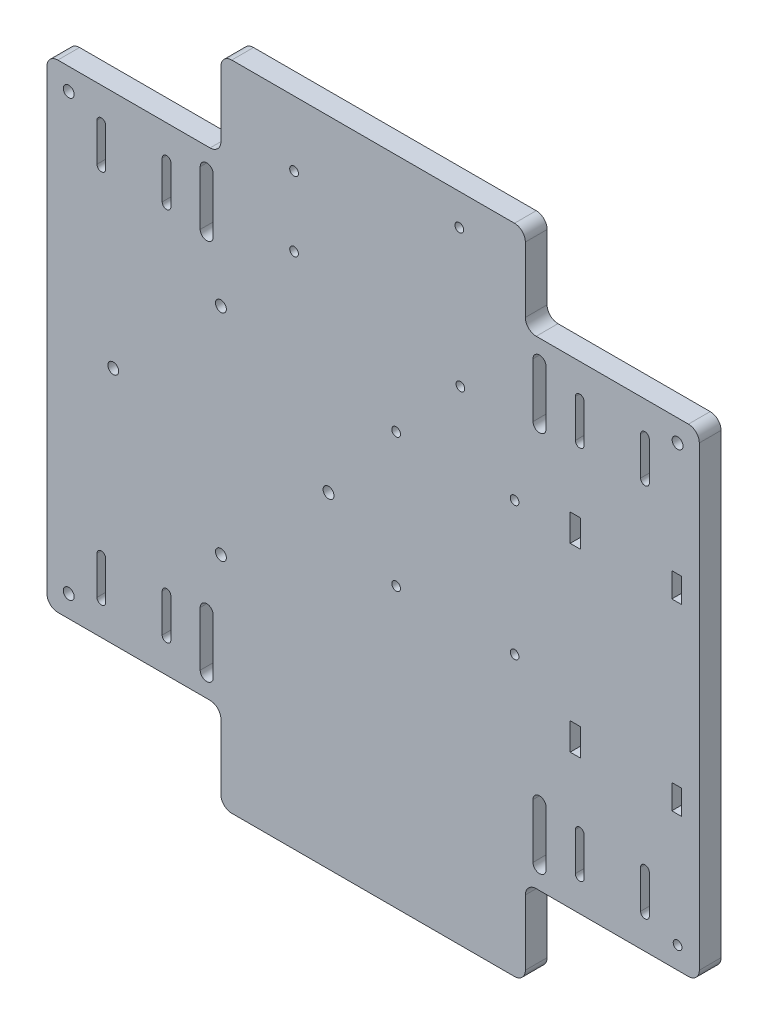
SolidWorks part; units mm, degrees
ref_plane "前视基准面" through (0, 0, 0) normal (0, 0, 1) x (1, 0, 0)
ref_plane "上视基准面" through (0, 0, 0) normal (0, 1, 0) x (1, 0, 0)
ref_plane "右视基准面" through (0, 0, 0) normal (1, 0, 0) x (0, 0, -1)
other "Configuration Table"
sketch "草图1" plane through (0, 0, 0) normal (0, 0, 1) x (1, 0, 0)
  line L0 (-0.0293, 147.9876) -> (299.9707, 147.9876) construction
  line L1 (84.9707, -2.0124) -> (214.9707, -2.0124)
  line L2 (-0.0293, 42.9876) -> (-0.0293, 252.9876)
  line L3 (84.9707, 297.9876) -> (214.9707, 297.9876)
  line L4 (299.9707, 42.9876) -> (299.9707, 252.9876)
  line L7 (4.9707, 37.9876) -> (74.9707, 37.9876)
  line L8 (79.9707, 2.9876) -> (79.9707, 32.9876)
  line L9 (149.9707, 297.9876) -> (149.9707, -2.0124) construction
  line L10 (4.9707, 257.9876) -> (74.9707, 257.9876)
  line L11 (79.9707, 292.9876) -> (79.9707, 262.9876)
  line L14 (294.9707, 37.9876) -> (224.9707, 37.9876)
  line L15 (219.9707, 2.9876) -> (219.9707, 32.9876)
  line L19 (219.9707, 292.9876) -> (219.9707, 262.9876)
  line L20 (294.9707, 257.9876) -> (224.9707, 257.9876)
  line L22 (24.9707, 242.9876) -> (54.9707, 242.9876) construction
  line L23 (24.9707, 242.9876) -> (24.9707, 225.4876) construction
  line L24 (24.9707, 225.4876) -> (54.9707, 225.4876) construction
  line L25 (54.9707, 242.9876) -> (54.9707, 225.4876) construction
  line L26 (244.9707, 242.9876) -> (244.9707, 225.4876) construction
  line L27 (274.9707, 242.9876) -> (244.9707, 242.9876) construction
  line L28 (274.9707, 242.9876) -> (274.9707, 225.4876) construction
  line L29 (274.9707, 225.4876) -> (244.9707, 225.4876) construction
  line L30 (274.9707, 52.9876) -> (244.9707, 52.9876) construction
  line L31 (244.9707, 52.9876) -> (244.9707, 70.4876) construction
  line L32 (274.9707, 70.4876) -> (244.9707, 70.4876) construction
  line L33 (274.9707, 52.9876) -> (274.9707, 70.4876) construction
  line L34 (54.9707, 52.9876) -> (54.9707, 70.4876) construction
  line L35 (24.9707, 52.9876) -> (54.9707, 52.9876) construction
  line L36 (24.9707, 52.9876) -> (24.9707, 70.4876) construction
  line L37 (79.9707, 297.9876) -> (79.9707, 262.9876)
  line L38 (-0.0293, 257.9876) -> (74.9707, 257.9876)
  line L39 (-0.0293, 37.9876) -> (74.9707, 37.9876)
  line L40 (79.9707, -2.0124) -> (79.9707, 32.9876)
  line L41 (79.9707, -2.0124) -> (219.9707, -2.0124)
  line L42 (219.9707, -2.0124) -> (219.9707, 32.9876)
  line L43 (299.9707, 37.9876) -> (224.9707, 37.9876)
  line L44 (299.9707, 257.9876) -> (224.9707, 257.9876)
  line L45 (219.9707, 297.9876) -> (219.9707, 262.9876)
  line L46 (79.9707, 297.9876) -> (219.9707, 297.9876)
  line L47 (24.9707, 70.4876) -> (54.9707, 70.4876) construction
  line L48 (234.9707, 204.4876) -> (284.9707, 204.4876) construction
  line L49 (234.9707, 37.9876) -> (284.9707, 37.9876) construction
  line L50 (234.9707, 37.9876) -> (234.9707, 91.4876) construction
  line L51 (234.9707, 91.4876) -> (284.9707, 91.4876) construction
  line L52 (284.9707, 37.9876) -> (284.9707, 91.4876) construction
  line L53 (284.9707, 257.9876) -> (284.9707, 204.4876) construction
  line L54 (234.9707, 257.9876) -> (284.9707, 257.9876) construction
  line L55 (234.9707, 257.9876) -> (234.9707, 204.4876) construction
  line L56 (64.9707, 91.4876) -> (14.9707, 91.4876) construction
  line L57 (14.9707, 37.9876) -> (14.9707, 91.4876) construction
  line L58 (64.9707, 37.9876) -> (14.9707, 37.9876) construction
  line L59 (64.9707, 37.9876) -> (64.9707, 91.4876) construction
  line L60 (64.9707, 257.9876) -> (64.9707, 204.4876) construction
  line L61 (64.9707, 257.9876) -> (14.9707, 257.9876) construction
  line L62 (14.9707, 257.9876) -> (14.9707, 204.4876) construction
  line L63 (64.9707, 204.4876) -> (14.9707, 204.4876) construction
  line L64 (287.3162, 100.1548) -> (291.8708, 100.1548)
  line L65 (245.3162, 222.9876) -> (287.3162, 222.9876) construction
  line L66 (245.3162, 222.9876) -> (245.3162, 72.9876) construction
  line L67 (245.3162, 72.9876) -> (287.3162, 72.9876) construction
  line L68 (287.3162, 222.9876) -> (287.3162, 72.9876) construction
  line L69 (245.3162, 195.8204) -> (240.5982, 195.8204)
  line L70 (245.3162, 195.8204) -> (245.3162, 183.3094)
  line L71 (245.3162, 183.3094) -> (240.5982, 183.3094)
  line L72 (240.5982, 195.8204) -> (240.5982, 183.3094)
  line L73 (287.3162, 184.5393) -> (291.8708, 184.5393)
  line L74 (287.3162, 184.5393) -> (287.3162, 195.8204)
  line L75 (287.3162, 195.8204) -> (291.8708, 195.8204)
  line L76 (291.8708, 184.5393) -> (291.8708, 195.8204)
  line L77 (291.8708, 111.4358) -> (291.8708, 100.1548)
  line L78 (287.3162, 111.4358) -> (291.8708, 111.4358)
  line L79 (287.3162, 111.4358) -> (287.3162, 100.1548)
  line L80 (245.3162, 112.6658) -> (240.5982, 112.6658)
  line L81 (240.5982, 100.1548) -> (240.5982, 112.6658)
  line L82 (245.3162, 100.1548) -> (240.5982, 100.1548)
  line L83 (245.3162, 100.1548) -> (245.3162, 112.6658)
  line L84 (194.1063, 224.0826) -> (202.6063, 224.0826) construction
  line L85 (117.6063, 280.0826) -> (185.6063, 280.0826) construction
  line L86 (117.6063, 280.0826) -> (117.6063, 272.0826) construction
  line L87 (117.6063, 224.0826) -> (185.6063, 224.0826) construction
  line L88 (202.6063, 280.0826) -> (202.6063, 224.0826) construction
  line L90 (185.6063, 280.0826) -> (185.6063, 287.5826) construction
  line L91 (185.6063, 287.5826) -> (194.1063, 287.5826) construction
  line L92 (194.1063, 280.0826) -> (194.1063, 287.5826) construction
  line L94 (194.1063, 224.0826) -> (194.1063, 216.5826) construction
  line L95 (194.1063, 216.5826) -> (185.6063, 216.5826) construction
  line L96 (185.6063, 224.0826) -> (185.6063, 216.5826) construction
  line L97 (117.6063, 272.0826) -> (109.6063, 272.0826) construction
  line L99 (117.6063, 264.0826) -> (109.6063, 264.0826) construction
  line L100 (109.6063, 272.0826) -> (109.6063, 264.0826) construction
  line L101 (117.6063, 240.0826) -> (109.6063, 240.0826) construction
  line L103 (117.6063, 232.0826) -> (109.6063, 232.0826) construction
  line L104 (109.6063, 240.0826) -> (109.6063, 232.0826) construction
  line L105 (194.1063, 280.0826) -> (202.6063, 280.0826) construction
  line L106 (117.6063, 264.0826) -> (117.6063, 240.0826) construction
  line L107 (117.6063, 232.0826) -> (117.6063, 224.0826) construction
  line L108 (24.9707, 70.4876) -> (24.9707, 52.9876) construction
  line L109 (157.7933, 191.5114) -> (217.7933, 191.5114) construction
  line L110 (157.7933, 191.5114) -> (157.7933, 122.5114) construction
  line L111 (157.7933, 122.5114) -> (217.7933, 122.5114) construction
  line L112 (217.7933, 191.5114) -> (217.7933, 122.5114) construction
  line L113 (26.9707, 70.4876) -> (26.9707, 52.9876)
  line L114 (22.9707, 70.4876) -> (22.9707, 52.9876)
  line L115 (54.9707, 70.4876) -> (54.9707, 52.9876) construction
  line L116 (56.9707, 70.4876) -> (56.9707, 52.9876)
  line L117 (52.9707, 70.4876) -> (52.9707, 52.9876)
  line L118 (244.9707, 70.4876) -> (244.9707, 52.9876) construction
  line L119 (246.9707, 70.4876) -> (246.9707, 52.9876)
  line L120 (242.9707, 70.4876) -> (242.9707, 52.9876)
  line L121 (274.9707, 52.9876) -> (274.9707, 70.4876) construction
  line L122 (272.9707, 52.9876) -> (272.9707, 70.4876)
  line L123 (276.9707, 52.9876) -> (276.9707, 70.4876)
  line L124 (24.9707, 225.4876) -> (24.9707, 242.9876) construction
  line L125 (26.9707, 225.4876) -> (26.9707, 242.9876)
  line L126 (22.9707, 225.4876) -> (22.9707, 242.9876)
  line L127 (54.9707, 225.4876) -> (54.9707, 242.9876) construction
  line L128 (56.9707, 225.4876) -> (56.9707, 242.9876)
  line L129 (52.9707, 225.4876) -> (52.9707, 242.9876)
  line L130 (244.9707, 225.4876) -> (244.9707, 242.9876) construction
  line L131 (246.9707, 225.4876) -> (246.9707, 242.9876)
  line L132 (242.9707, 225.4876) -> (242.9707, 242.9876)
  line L133 (274.9707, 242.9876) -> (274.9707, 225.4876) construction
  line L134 (272.9707, 242.9876) -> (272.9707, 225.4876)
  line L135 (276.9707, 242.9876) -> (276.9707, 225.4876)
  line L136 (157.7933, 157.0114) -> (217.7933, 157.0114) construction
  line L137 (226.4945, 248.2611) -> (226.4945, 223.2611) construction
  line L140 (229.4945, 248.2611) -> (229.4945, 223.2611)
  line L143 (223.4945, 248.2611) -> (223.4945, 223.2611)
  line L146 (73.4468, 248.2611) -> (73.4468, 223.2611) construction
  line L149 (70.4468, 248.2611) -> (70.4468, 223.2611)
  line L150 (76.4468, 248.2611) -> (76.4468, 223.2611)
  line L151 (73.4468, 47.7141) -> (73.4468, 72.7141) construction
  line L152 (70.4468, 47.7141) -> (70.4468, 72.7141)
  line L153 (76.4468, 47.7141) -> (76.4468, 72.7141)
  line L154 (226.4945, 47.7141) -> (226.4945, 72.7141) construction
  line L155 (229.4945, 47.7141) -> (229.4945, 72.7141)
  line L156 (223.4945, 47.7141) -> (223.4945, 72.7141)
  circle A0 centre (79.9707, 147.9876) radius 60 construction
  circle A1 centre (79.9707, 147.9876) radius 49.5 construction
  circle A2 centre (129.4707, 147.9876) radius 2.5
  circle A3 centre (79.9707, 98.4876) radius 2.5
  circle A4 centre (30.4707, 147.9876) radius 2.5
  circle A5 centre (79.9707, 197.4876) radius 2.5
  circle A22 centre (9.9707, 247.9876) radius 2.5
  circle A24 centre (289.9707, 47.9876) radius 2
  circle A25 centre (9.9707, 47.9876) radius 2.5
  circle A26 centre (113.6063, 268.0826) radius 2
  circle A27 centre (113.6063, 236.0826) radius 2
  circle A28 centre (190.1063, 220.5826) radius 2
  circle A29 centre (189.6063, 283.5826) radius 2
  circle A32 centre (215.0333, 187.7214) radius 2
  circle A33 centre (160.5533, 187.7214) radius 2
  circle A34 centre (289.9707, 247.9876) radius 2.5
  arc A35 (26.9707, 70.4876) -> (22.9707, 70.4876) centre (24.9707, 70.4876) ccw
  arc A36 (22.9707, 52.9876) -> (26.9707, 52.9876) centre (24.9707, 52.9876) ccw
  arc A37 (56.9707, 70.4876) -> (52.9707, 70.4876) centre (54.9707, 70.4876) ccw
  arc A38 (52.9707, 52.9876) -> (56.9707, 52.9876) centre (54.9707, 52.9876) ccw
  arc A39 (246.9707, 70.4876) -> (242.9707, 70.4876) centre (244.9707, 70.4876) ccw
  arc A40 (242.9707, 52.9876) -> (246.9707, 52.9876) centre (244.9707, 52.9876) ccw
  arc A41 (272.9707, 52.9876) -> (276.9707, 52.9876) centre (274.9707, 52.9876) ccw
  arc A42 (276.9707, 70.4876) -> (272.9707, 70.4876) centre (274.9707, 70.4876) ccw
  arc A43 (26.9707, 225.4876) -> (22.9707, 225.4876) centre (24.9707, 225.4876) cw
  arc A44 (22.9707, 242.9876) -> (26.9707, 242.9876) centre (24.9707, 242.9876) cw
  arc A45 (56.9707, 225.4876) -> (52.9707, 225.4876) centre (54.9707, 225.4876) cw
  arc A46 (52.9707, 242.9876) -> (56.9707, 242.9876) centre (54.9707, 242.9876) cw
  arc A47 (246.9707, 225.4876) -> (242.9707, 225.4876) centre (244.9707, 225.4876) cw
  arc A48 (242.9707, 242.9876) -> (246.9707, 242.9876) centre (244.9707, 242.9876) cw
  arc A49 (272.9707, 242.9876) -> (276.9707, 242.9876) centre (274.9707, 242.9876) cw
  arc A50 (276.9707, 225.4876) -> (272.9707, 225.4876) centre (274.9707, 225.4876) cw
  circle A51 centre (215.0333, 126.3014) radius 2
  circle A52 centre (160.5533, 126.3014) radius 2
  arc A53 (4.9707, 257.9876) -> (-0.0293, 252.9876) centre (4.9707, 252.9876) ccw
  arc A54 (74.9707, 37.9876) -> (79.9707, 32.9876) centre (74.9707, 32.9876) cw
  arc A55 (-0.0293, 42.9876) -> (4.9707, 37.9876) centre (4.9707, 42.9876) ccw
  arc A56 (84.9707, -2.0124) -> (79.9707, 2.9876) centre (84.9707, 2.9876) cw
  arc A57 (219.9707, 2.9876) -> (214.9707, -2.0124) centre (214.9707, 2.9876) cw
  arc A58 (224.9707, 37.9876) -> (219.9707, 32.9876) centre (224.9707, 32.9876) ccw
  arc A59 (294.9707, 37.9876) -> (299.9707, 42.9876) centre (294.9707, 42.9876) ccw
  arc A60 (294.9707, 257.9876) -> (299.9707, 252.9876) centre (294.9707, 252.9876) cw
  arc A61 (219.9707, 262.9876) -> (224.9707, 257.9876) centre (224.9707, 262.9876) ccw
  arc A62 (214.9707, 297.9876) -> (219.9707, 292.9876) centre (214.9707, 292.9876) cw
  arc A63 (79.9707, 292.9876) -> (84.9707, 297.9876) centre (84.9707, 292.9876) cw
  arc A72 (229.4945, 248.2611) -> (223.4945, 248.2611) centre (226.4945, 248.2611) ccw
  arc A73 (223.4945, 223.2611) -> (229.4945, 223.2611) centre (226.4945, 223.2611) ccw
  arc A74 (70.4468, 248.2611) -> (76.4468, 248.2611) centre (73.4468, 248.2611) cw
  arc A75 (76.4468, 223.2611) -> (70.4468, 223.2611) centre (73.4468, 223.2611) cw
  arc A76 (70.4468, 47.7141) -> (76.4468, 47.7141) centre (73.4468, 47.7141) ccw
  arc A77 (76.4468, 72.7141) -> (70.4468, 72.7141) centre (73.4468, 72.7141) ccw
  arc A78 (229.4945, 47.7141) -> (223.4945, 47.7141) centre (226.4945, 47.7141) cw
  arc A79 (223.4945, 72.7141) -> (229.4945, 72.7141) centre (226.4945, 72.7141) cw
  arc A80 (74.9707, 257.9876) -> (79.9707, 262.9876) centre (74.9707, 262.9876) ccw
  point P44 (244.9707, 61.7376)
  point P55 (24.9707, 61.7376)
  point P144 (54.9707, 61.7376)
  point P150 (274.9707, 61.7376)
  point P155 (24.9707, 234.2376)
  point P160 (54.9707, 234.2376)
  point P165 (244.9707, 234.2376)
  point P170 (274.9707, 234.2376)
  point P204 (226.4945, 235.7611)
  point P211 (73.4468, 235.7611)
  point P218 (73.4468, 60.2141)
  point P225 (226.4945, 60.2141)
  dimension "D1" = 120
  dimension "D2" = 80
  dimension "D5" = 99
  dimension "D6" = 5
  dimension "D7" = 4
  dimension "D11" = 2.76
  dimension "D12" = 54.48
  dimension "D13" = 5
  dimension "D14" = 25
  dimension "D25" = 5
  dimension "D42" = 4
  dimension "D43" = 4
  dimension "D44" = 4
  dimension "D45" = 4
  dimension "D56" = 4
  dimension "D57" = 4
  dimension "D58" = 3
  dimension "D59" = 300
  dimension "D68" = 5
  dimension "D69" = 4
  dimension "D70" = 2
  dimension "D71" = 2
  dimension "D72" = 2
  dimension "D73" = 2
  dimension "D60" = 5
  dimension "D22" = 2
  dimension "D8" = 17.5
  dimension "D9" = 15
  dimension "D10" = 25
  dimension "D15" = 50
  dimension "D16" = 53.5
  dimension "D17" = 15
  dimension "D18" = 30
  dimension "D19" = 30
  dimension "D20" = 150
  dimension "D21" = 42
  dimension "D23" = 220
  dimension "D24" = 75
  dimension "D26" = 10
  dimension "D27" = 10
  dimension "D28" = 56
  dimension "D29" = 85
  dimension "D30" = 7.5
  dimension "D31" = 8.5
  dimension "D32" = 8.5
  dimension "D33" = 7.5
  dimension "D34" = 8.5
  dimension "D35" = 8.5
  dimension "D36" = 24
  dimension "D37" = 8
  dimension "D38" = 8
  dimension "D39" = 8
  dimension "D40" = 8
  dimension "D41" = 8
  dimension "D46" = 4
  dimension "D47" = 4
  dimension "D48" = 4
  dimension "D49" = 4
  dimension "D50" = 4
  dimension "D51" = 4
  dimension "D52" = 4
  dimension "D53" = 4
  dimension "D54" = 60
  dimension "D55" = 69
  dimension "D64" = 3.79
  dimension "D66" = 3.79
  dimension "D67" = 2.76
extrude "凸台-拉伸1" add sketch "草图1" along normal blind 10
